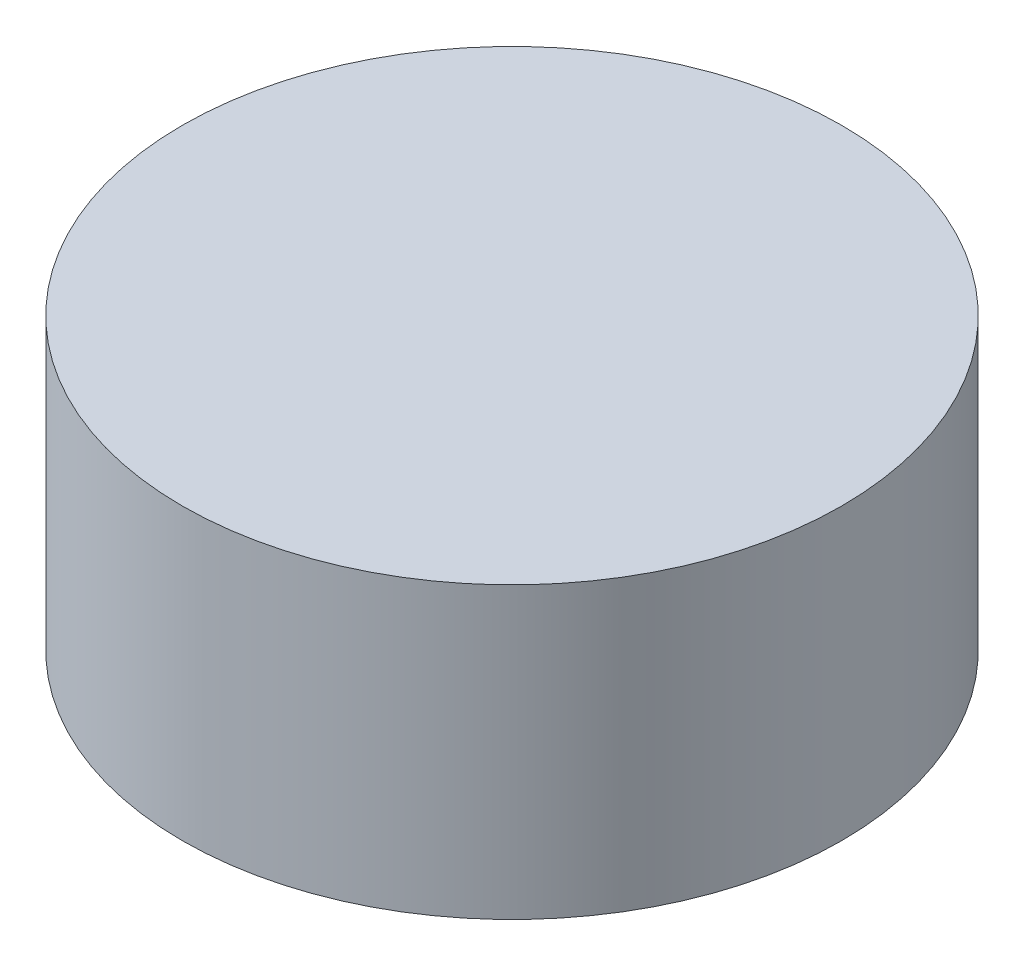
SolidWorks part; units mm, degrees
ref_plane "정면" through (0, 0, 0) normal (0, 0, 1) x (1, 0, 0)
ref_plane "윗면" through (0, 0, 0) normal (0, 1, 0) x (1, 0, 0)
ref_plane "우측면" through (0, 0, 0) normal (1, 0, 0) x (0, 0, -1)
sketch "스케치1" plane through (0, 0, 0) normal (0, 1, 0) x (1, 0, 0)
  circle A0 centre (0, 0) radius 2.275
  dimension "D1" = 4.55
extrude "보스-돌출1" add sketch "스케치1" along normal blind 2
